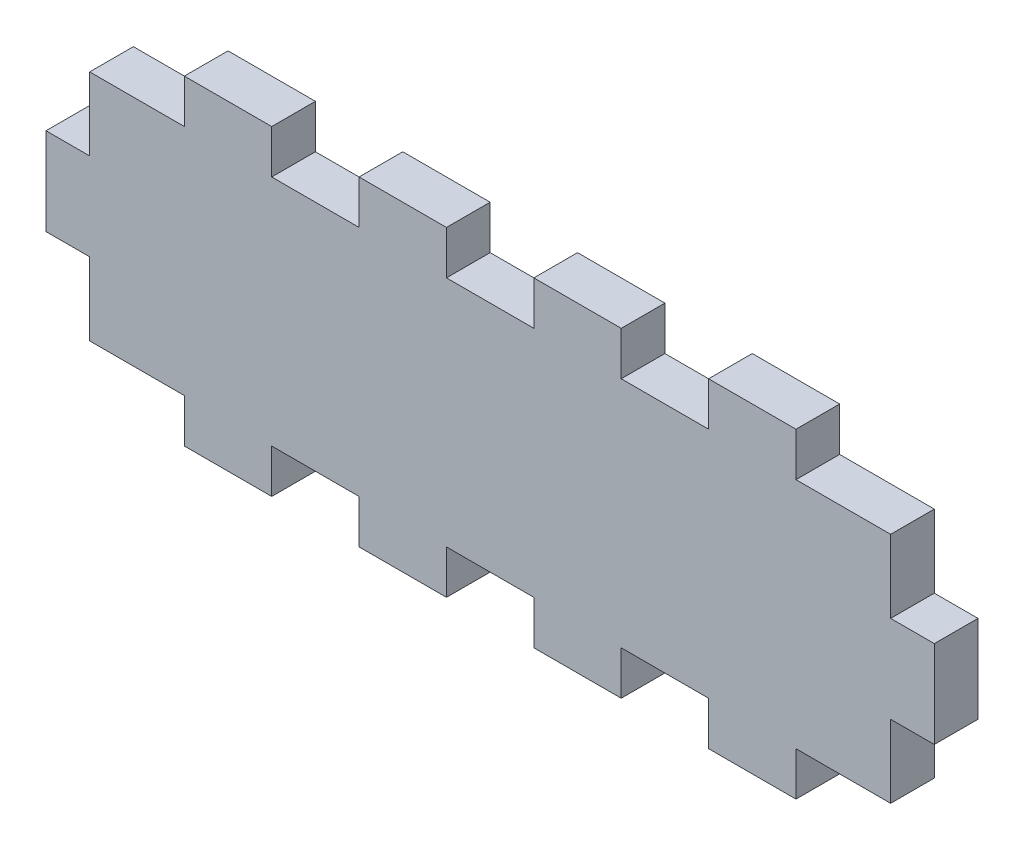
SolidWorks part; units mm, degrees
material "PMMA"
ref_plane "前视基准面" through (0, 0, 0) normal (0, 0, 1) x (1, 0, 0)
ref_plane "上视基准面" through (0, 0, 0) normal (0, 1, 0) x (1, 0, 0)
ref_plane "右视基准面" through (0, 0, 0) normal (1, 0, 0) x (0, 0, -1)
other "Configuration Table"
sketch "Model" plane through (0, 0, 0) normal (0, 0, 1) x (1, 0, 0)
  line L0 (92, 47) -> (92, 42)
  line L1 (92, 42) -> (89, 42)
  line L2 (89, 42) -> (89, 36)
  line L3 (89, 36) -> (92, 36)
  line L4 (92, 36) -> (92, 31)
  line L5 (92, 31) -> (98.5, 31)
  line L6 (98.5, 31) -> (98.5, 28)
  line L7 (98.5, 28) -> (104.5, 28)
  line L8 (104.5, 28) -> (104.5, 31)
  line L9 (104.5, 31) -> (110.5, 31)
  line L10 (110.5, 31) -> (110.5, 28)
  line L11 (110.5, 28) -> (116.5, 28)
  line L12 (116.5, 28) -> (116.5, 31)
  line L13 (116.5, 31) -> (122.5, 31)
  line L14 (122.5, 31) -> (122.5, 28)
  line L15 (122.5, 28) -> (128.5, 28)
  line L16 (128.5, 28) -> (128.5, 31)
  line L17 (128.5, 31) -> (134.5, 31)
  line L18 (134.5, 31) -> (134.5, 28)
  line L19 (134.5, 28) -> (140.5, 28)
  line L20 (140.5, 28) -> (140.5, 31)
  line L21 (140.5, 31) -> (146.5, 31)
  line L22 (146.5, 31) -> (147, 31)
  line L23 (147, 31) -> (147, 36)
  line L24 (147, 36) -> (150, 36)
  line L25 (150, 36) -> (150, 42)
  line L26 (150, 42) -> (147, 42)
  line L27 (147, 42) -> (147, 47)
  line L28 (147, 47) -> (140.5, 47)
  line L29 (140.5, 47) -> (140.5, 50)
  line L30 (140.5, 50) -> (134.5, 50)
  line L31 (134.5, 50) -> (134.5, 47)
  line L32 (134.5, 47) -> (128.5, 47)
  line L33 (128.5, 47) -> (128.5, 50)
  line L34 (128.5, 50) -> (122.5, 50)
  line L35 (122.5, 50) -> (122.5, 47)
  line L36 (122.5, 47) -> (116.5, 47)
  line L37 (116.5, 47) -> (116.5, 50)
  line L38 (116.5, 50) -> (110.5, 50)
  line L39 (110.5, 50) -> (110.5, 47)
  line L40 (110.5, 47) -> (104.5, 47)
  line L41 (104.5, 47) -> (104.5, 50)
  line L42 (104.5, 50) -> (98.5, 50)
  line L43 (98.5, 50) -> (98.5, 47)
  line L44 (98.5, 47) -> (92.5, 47)
  line L45 (92.5, 47) -> (92, 47)
extrude "凸台-拉伸1" add sketch "Model" along normal blind 3
